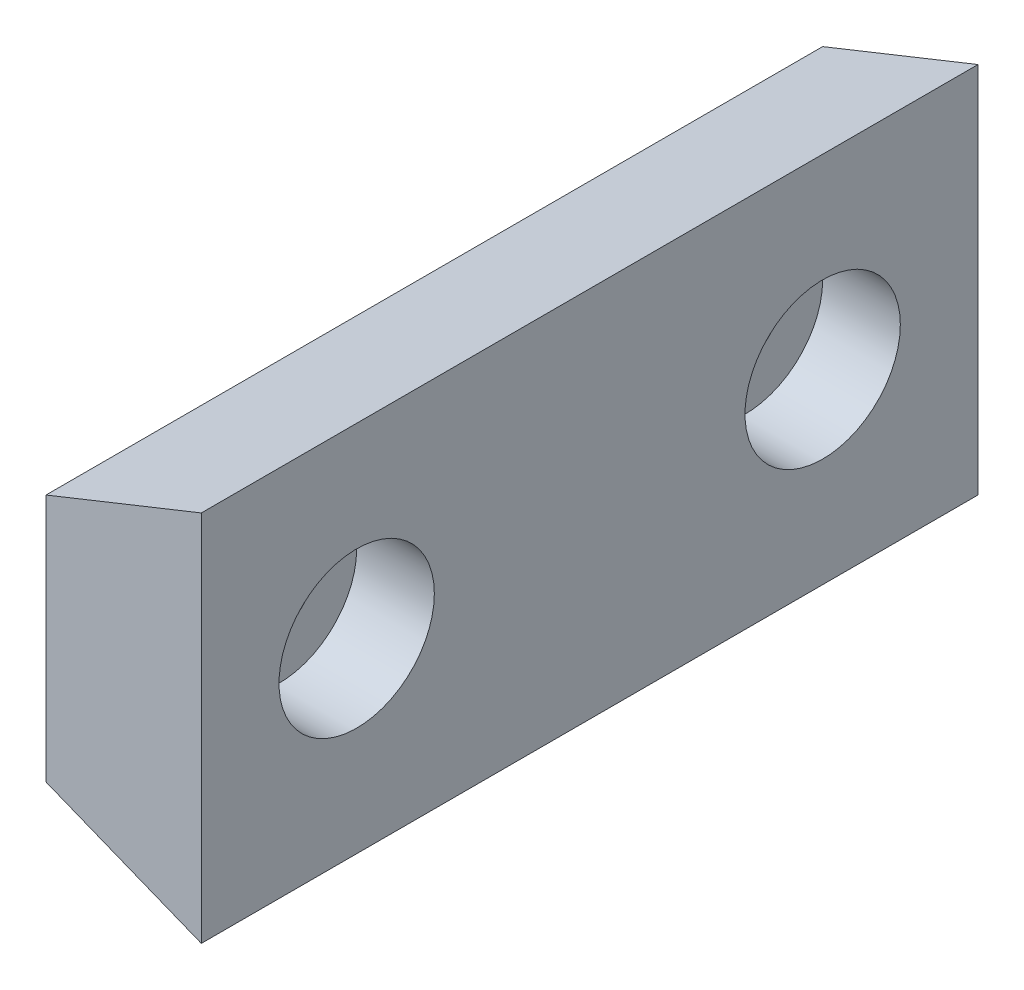
SolidWorks part; units mm, degrees
ref_plane "Plano frontal" through (0, 0, 0) normal (1, 0, 0) x (0, 1, 0)
ref_plane "Plano superior" through (0, 0, 0) normal (0, 0, 1) x (0, 1, 0)
ref_plane "Plano direito" through (0, 0, 0) normal (0, 1, 0) x (-1, 0, 0)
sketch "Esboço1" plane through (0, 0, 0) normal (0, 0, 1) x (0, 1, 0)
  line L0 (-6, 0) -> (6, 0)
  line L1 (6, 0) -> (4, 5)
  line L2 (4, 5) -> (-4, 5)
  line L3 (-4, 5) -> (-6, 0)
  point P3 (7.7028, 14.0155)
  point P6 (0, 5)
  dimension "D1" = 8
  dimension "D2" = 12
  dimension "D3" = 5
extrude "Ressalto-extrusão1" add sketch "Esboço1" along normal blind 25
sketch "Esboço2" plane through (0, 0, 0) normal (1, 0, 0) x (0, 1, 0)
  line L0 (0, 20) -> (0, 5) construction
  line L1 (-6, 25) -> (-6, 0) construction
  circle A0 centre (0, 20) radius 1.05
  circle A1 centre (0, 5) radius 1.05
  point P4 (0, 12.5)
  point P5 (0, 4.8478)
  point P9 (-6, 12.5)
  dimension "D2" = 2.1
  dimension "D1" = 15
extrude "Corte-extrusão1" cut sketch "Esboço2" against normal blind 20
sketch "Esboço3" plane through (0, 0, 0) normal (1, 0, 0) x (0, 1, 0)
  circle A0 centre (0, 20) radius 2.5
  circle A1 centre (0, 5) radius 2.5
  dimension "D1" = 5
extrude "Corte-extrusão3" cut sketch "Esboço3" against normal blind 2.5
